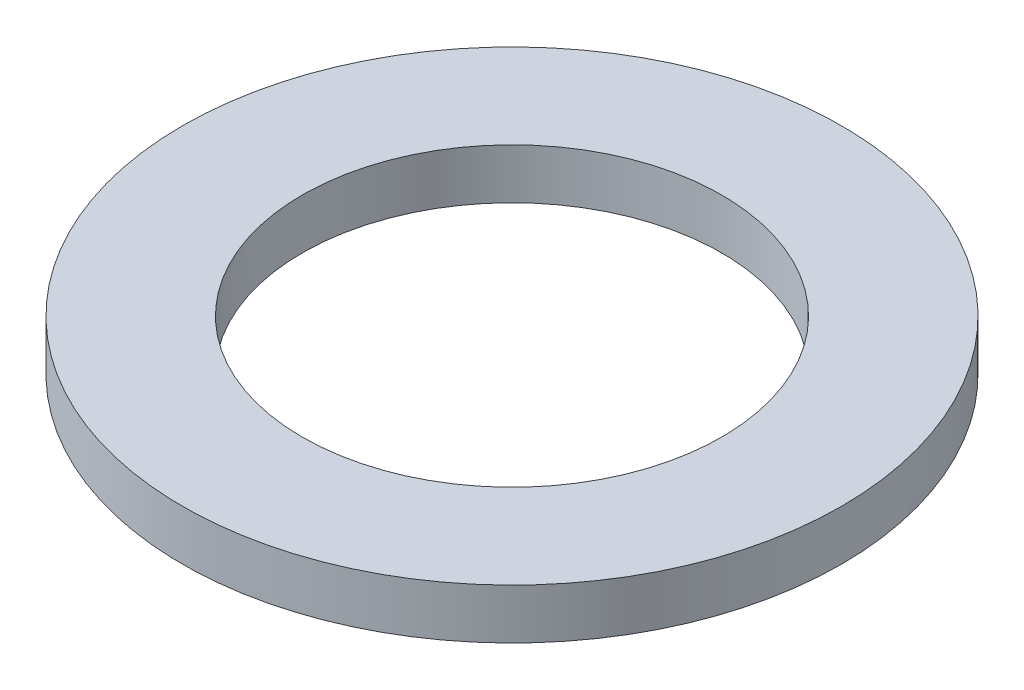
SolidWorks part; units mm, degrees
ref_plane "Front Plane" through (0, 0, 0) normal (0, 0, 1) x (1, 0, 0)
ref_plane "Top Plane" through (0, 0, 0) normal (0, 1, 0) x (1, 0, 0)
ref_plane "Right Plane" through (0, 0, 0) normal (1, 0, 0) x (0, 0, -1)
sketch "Sketch2" plane through (0, 0, 0) normal (0, 1, 0) x (1, 0, 0)
  circle A0 centre (0, 0) radius 14
  dimension "D1" = 28
extrude "Extrude-Thin1" add sketch "Sketch2" along normal blind 3.35 thin
